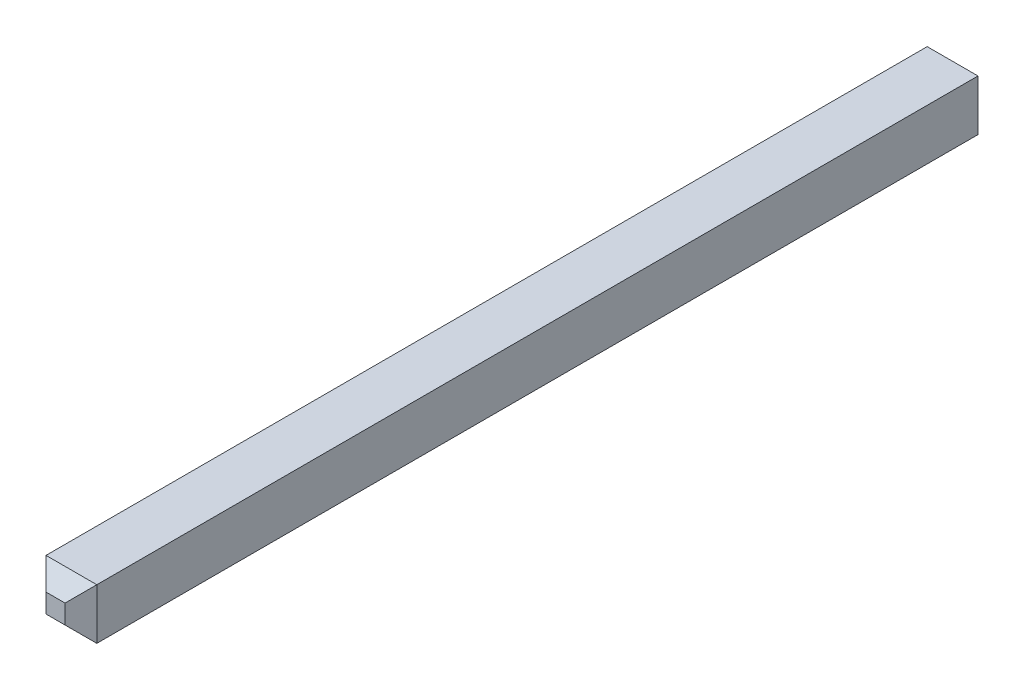
SolidWorks part; units mm, degrees
other "Детальный элемент1"
ref_plane "Спереди" through (0, 0, 0) normal (0, 0, 1) x (1, 0, 0)
ref_plane "Сверху" through (0, 0, 0) normal (0, 1, 0) x (1, 0, 0)
ref_plane "Справа" through (0, 0, 0) normal (1, 0, 0) x (0, 0, -1)
sketch "Эскиз1" plane through (0, 0, 0) normal (0, 0, 1) x (1, 0, 0)
  line L1 (-0.32, 0.32) -> (0.32, 0.32)
  line L2 (-0.32, 0.32) -> (-0.32, -0.32)
  line L3 (-0.32, -0.32) -> (0.32, -0.32)
  line L4 (0.32, 0.32) -> (0.32, -0.32)
  line L5 (-0.32, 0.32) -> (0.32, -0.32) construction
  line L6 (-0.32, -0.32) -> (0.32, 0.32) construction
  point P0 (0, 0)
  dimension "D1" = 0.64
extrude "Бобышка-Вытянуть1" add sketch "Эскиз1" along normal blind 8 and the other way blind 3.5
chamfer "Фаска1" distance 0.2 angle 45 8 edges at (0.32, 0, 8) (0, 0.32, 8) (-0.32, 0, 8) (0, -0.32, 8) (0, 0.32, -3.5) (-0.32, 0, -3.5) (0.32, 0, -3.5) (0, -0.32, -3.5)
